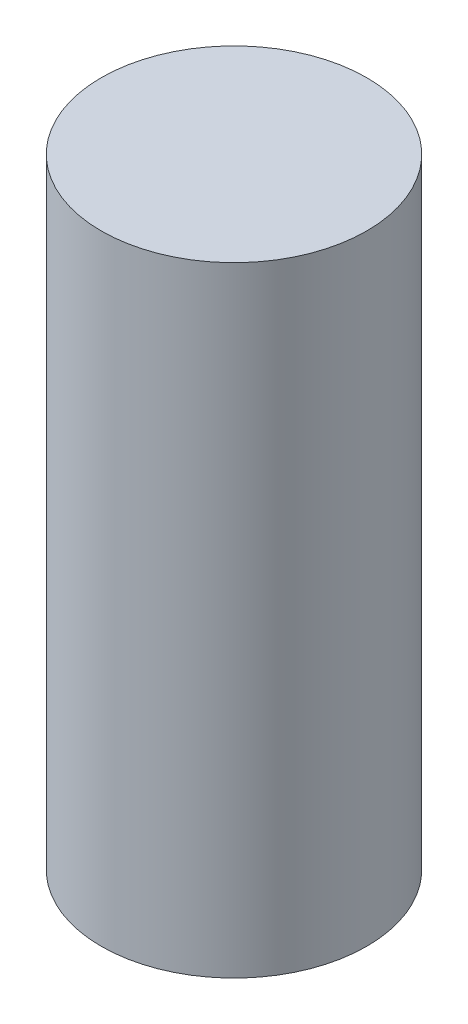
SolidWorks part; units mm, degrees
ref_plane "Front Plane" through (0, 0, 0) normal (0, 0, 1) x (1, 0, 0)
ref_plane "Top Plane" through (0, 0, 0) normal (0, 1, 0) x (1, 0, 0)
ref_plane "Right Plane" through (0, 0, 0) normal (1, 0, 0) x (0, 0, -1)
other "Configuration Table"
sketch "Sketch1" plane through (0, 0, 0) normal (0, 1, 0) x (1, 0, 0)
  circle A0 centre (50, 770) radius 6
extrude "TOPPING_ayar_mil_3" add sketch "Sketch1" along normal blind 28 from offset 12 separate body
